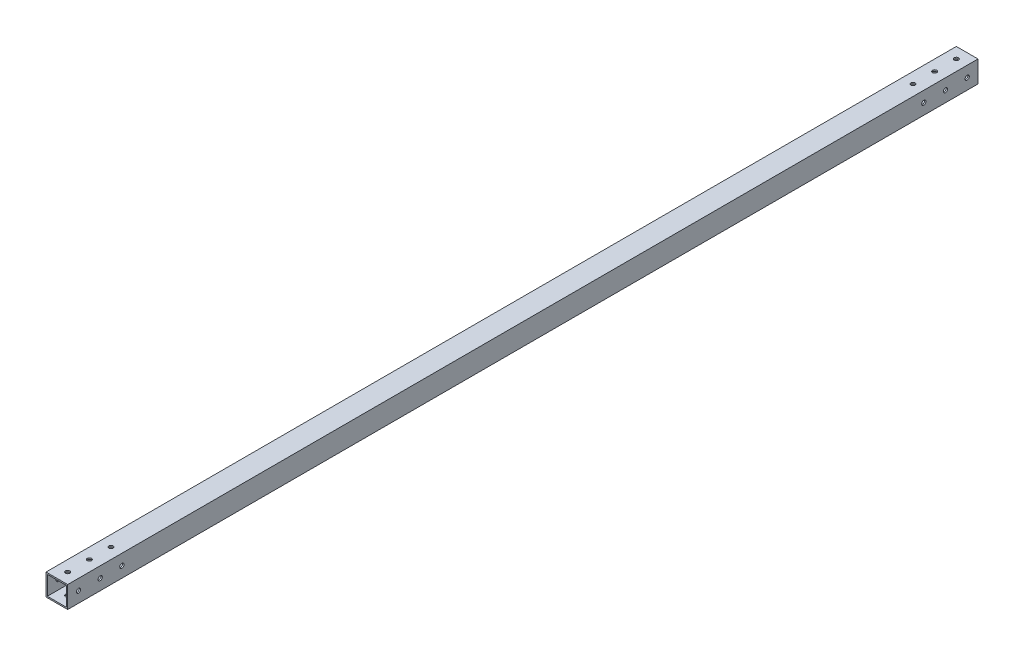
SolidWorks part; units mm, degrees
material "6061-T6 (SS)"
ref_plane "Front Plane" through (0, 0, 0) normal (0, 0, 1) x (1, 0, 0)
ref_plane "Top Plane" through (0, 0, 0) normal (0, 1, 0) x (1, 0, 0)
ref_plane "Right Plane" through (0, 0, 0) normal (1, 0, 0) x (0, 0, -1)
sketch "Sketch1" plane through (0, 0, 0) normal (0, 0, 1) x (1, 0, 0)
  line L1 (0, 0) -> (25.4, 0)
  line L2 (0, 0) -> (0, 25.4)
  line L3 (0, 25.4) -> (25.4, 25.4)
  line L4 (25.4, 0) -> (25.4, 25.4)
  dimension "D1" = 25.4
  dimension "D2" = 25.4
extrude "Boss-Extrude1" add sketch "Sketch1" along normal mid plane 1066.8
shell "Shell1" thickness 1.5875
sketch "Sketch3" plane through (0, 25.4, 0) normal (0, 1, 0) x (1, 0, 0)
  line L0 (25.4, -533.4) -> (0, -533.4) construction
  line L1 (0, -533.4) -> (0, 533.4) construction
  circle A0 centre (12.7, -520.7) radius 2.4892
  circle A1 centre (12.7, -495.3) radius 2.4892
  circle A2 centre (12.7, -469.9) radius 2.4892
  dimension "D1" = 4.9784
  dimension "D2" = 25.4
  dimension "D3" = 25.4
  dimension "D4" = 12.7
  dimension "D5" = 12.7
sketch "Sketch4" plane through (0, 0, 0) normal (-1, 0, 0) x (0, 0, 1)
  line L0 (533.4, 0) -> (-533.4, 0) construction
  line L1 (533.4, 25.4) -> (533.4, 0) construction
  circle A0 centre (520.7, 12.7) radius 2.4892
  circle A1 centre (495.3, 12.7) radius 2.4892
  circle A2 centre (469.9, 12.7) radius 2.4892
  dimension "D1" = 4.9784
  dimension "D2" = 25.4
  dimension "D3" = 25.4
  dimension "D4" = 12.7
  dimension "D5" = 12.7
extrude "Cut-Extrude1" cut sketch "Sketch3" against normal mid plane 1066.8
extrude "Cut-Extrude2" cut sketch "Sketch4" against normal mid plane 1066.8
mirror "Mirror1" about plane through (0, 0, 0) normal (0, 0, 1) of "Cut-Extrude2", "Cut-Extrude1"
